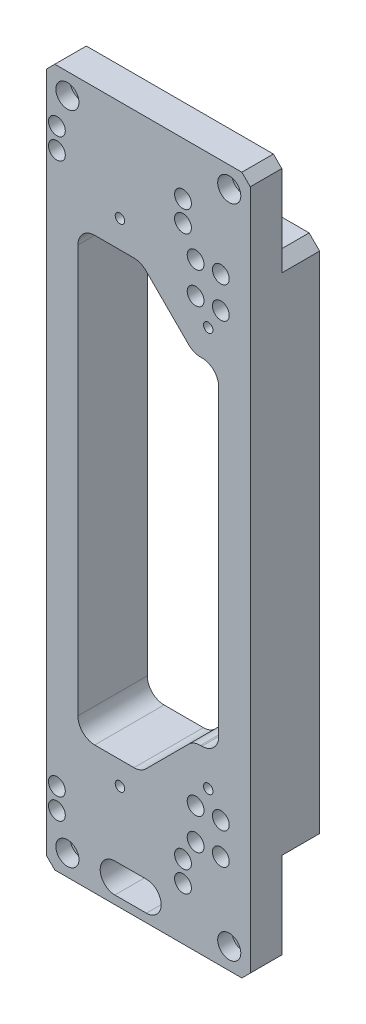
SolidWorks part; units mm, degrees
material "6061 Alloy"
ref_plane "Front Plane" through (0, 0, 0) normal (0, 0, 1) x (1, 0, 0)
ref_plane "Top Plane" through (0, 0, 0) normal (0, 1, 0) x (1, 0, 0)
ref_plane "Right Plane" through (0, 0, 0) normal (1, 0, 0) x (0, 0, -1)
sketch "Sketch1" plane through (0, 0, 0) normal (0, 0, 1) x (1, 0, 0)
  line L1 (48.5, -146) -> (-48.5, -146)
  line L2 (48.5, -146) -> (48.5, 146)
  line L3 (48.5, 146) -> (-48.5, 146)
  line L4 (-48.5, -146) -> (-48.5, 146)
  line L5 (48.5, -146) -> (-48.5, 146) construction
  line L6 (48.5, 146) -> (-48.5, -146) construction
  point P0 (0, 0)
  dimension "D1" = 292
  dimension "D3" = 97
extrude "Boss-Extrude1" add sketch "Sketch1" along normal blind 18 contours L4 L3 L2 L1
sketch "Sketch2" plane through (0, 0, 0) normal (0, 0, -1) x (-1, 0, 0)
  line L0 (-48.5, -146) -> (-48.5, 146) construction
  line L1 (-48.5, -146) -> (-21.5, -146)
  line L2 (-48.5, -146) -> (-48.5, -126)
  line L3 (-48.5, -126) -> (-21.5, -126)
  line L4 (-21.5, -146) -> (-21.5, -126)
  line L5 (-48.5, -146) -> (48.5, -146) construction
  line L6 (55, 0) -> (-55, 0) construction
  line L7 (-48.5, 124) -> (-21.5, 124)
  line L8 (-21.5, 146) -> (-21.5, 124)
  line L9 (-48.5, 146) -> (-21.5, 146)
  line L10 (-48.5, 146) -> (-48.5, 124)
  dimension "D1" = 20
  dimension "D2" = 27
  dimension "D3" = 22
extrude "Cut-Extrude1" cut sketch "Sketch2" against normal through all
sketch "Sketch3" plane through (0, 0, 18) normal (0, 0, 1) x (1, 0, 0)
  line L0 (-48.5, -146) -> (-48.5, 146) construction
  line L1 (48.5, -166) -> (-48.5, -166)
  line L2 (48.5, -166) -> (48.5, 166)
  line L3 (48.5, 166) -> (-48.5, 166)
  line L4 (-48.5, -166) -> (-48.5, 166)
  line L5 (48.5, -166) -> (-48.5, 166) construction
  line L6 (48.5, 166) -> (-48.5, -166) construction
  line L9 (21.5, 146) -> (-48.5, 146) construction
  point P0 (0, 0)
  dimension "D1" = 20
extrude "Boss-Extrude2" add sketch "Sketch3" along normal blind 15
chamfer "Chamfer1" distance 5 angle 45 6 edges at (21.5, -146, 9) (48.5, -126, 9) (21.5, 146, 9) (48.5, 124, 9) (-48.5, 146, 9) (-48.5, -146, 9)
fillet "Fillet1" radius 5 2 edges at (21.5, 124, 9) (21.5, -126, 9)
sketch "Sketch4" plane through (0, 0, 18) normal (0, 0, -1) x (-1, 0, 0)
  line L0 (0.9, -155) -> (15.9, -155) construction
  line L1 (0.9, -148) -> (15.9, -148)
  line L2 (0.9, -162) -> (15.9, -162)
  arc A0 (0.9, -148) -> (0.9, -162) centre (0.9, -155) ccw
  arc A1 (15.9, -162) -> (15.9, -148) centre (15.9, -155) ccw
  point P2 (8.4, -155)
  dimension "D2" = 7
  dimension "D1" = 15
  dimension "D3" = 155
  dimension "D4" = 8.4
extrude "Cut-Extrude2" cut sketch "Sketch4" against normal through all contours A1 L1 A0 L2
hole_wizard "CBORE for M4 Hexagon socket head cap screws1" positions "Sketch5" profile "Sketch6" counterbore size "M4" standard "GB" end condition through all
sketch "Sketch5" plane through (0, 0, 33) normal (0, 0, 1) x (1, 0, 0)
  line L0 (18.15, 0) -> (-18.15, 0) construction
  line L1 (-48.5, -1) -> (48.5, -1) construction
  line L2 (-48.5, 166) -> (-48.5, -166) construction
  line L3 (48.5, -166) -> (48.5, 166) construction
  point P0 (-43.5, -141)
  point P2 (-43.5, -131)
  point P4 (16.5, -131)
  point P6 (16.5, -141)
  point P11 (16.5, 141)
  point P12 (16.5, 131)
  point P13 (-43.5, 131)
  point P14 (-43.5, 141)
  point P24 (22.5, -121)
  point P26 (34.5, -121)
  point P28 (22.5, -106)
  point P30 (34.5, -106)
  point P49 (34.5, 104)
  point P50 (22.5, 104)
  point P51 (34.5, 119)
  point P52 (22.5, 119)
  dimension "D1" = 10
  dimension "D2" = 60
  dimension "D3" = 131
  dimension "D4" = 43.5
  dimension "D5" = 6
  dimension "D6" = 10
  dimension "D7" = 12
  dimension "D8" = 15
  dimension "D9" = 1
sketch "Sketch6" plane through (-43.5, -141, 33) normal (1, 0, 0) x (0, -1, 0)
  line L0 (0, 0) -> (0, 33)
  line L1 (0, 33) -> (2.25, 33)
  line L3 (2.25, 33) -> (2.25, 8)
  line L4 (2.25, 8) -> (4, 8)
  line L5 (4, 8) -> (4, 0)
  line L7 (4, 0) -> (0, 0)
  line L11 (0, -6.35) -> (0, 107.95) construction
  dimension "Thru Hole Dia." = 4.5
  dimension "Thru Hole Depth" = 33
  dimension "C'Bore Dia." = 8
  dimension "C'Bore Depth" = 8
hole_wizard "M4 Clearance Hole1" positions "Sketch7" profile "Sketch9" hole size "M4" standard "GB" end condition through all
sketch "Sketch7" plane through (0, 0, 33) normal (0, 0, 1) x (1, 0, 0)
  point P0 (28.5, -96)
  point P2 (-13.5, -116)
  point P4 (28.5, 94)
  point P6 (-13.5, 118)
  dimension "D1" = 94
  dimension "D2" = 96
  dimension "D3" = 116
  dimension "D4" = 118
  dimension "D5" = 13.5
  dimension "D6" = 28.5
sketch "Sketch9" plane through (28.5, -96, 33) normal (1, 0, 0) x (0, -1, 0)
  line L0 (0, 0) -> (0, 33)
  line L1 (0, 33) -> (2.25, 33)
  line L2 (2.25, 33) -> (2.25, 0)
  line L5 (2.25, 0) -> (0, 0)
  line L11 (0, -6.35) -> (0, 107.95) construction
  dimension "Thru Hole Dia." = 4.5
  dimension "Thru Hole Depth" = 33
hole_wizard "CBORE for M6 Slotted cheese head screws2" positions "Sketch10" profile "Sketch11" counterbore size "M6" standard "GB" end condition through all
sketch "Sketch10" plane through (0, 0, 33) normal (0, 0, 1) x (1, 0, 0)
  line L0 (18.15, 0) -> (-18.15, 0) construction
  line L1 (0, -18.15) -> (0, 18.15) construction
  line L2 (-48.5, 166) -> (-48.5, -166) construction
  line L4 (48.5, 166) -> (-48.5, 166) construction
  point P0 (-38.5, 156)
  point P8 (-38.5, -156)
  point P11 (38.5, -156)
  point P12 (38.5, 156)
  dimension "D1" = 10
  dimension "D2" = 10
sketch "Sketch11" plane through (-38.5, 156, 33) normal (1, 0, 0) x (0, -1, 0)
  line L0 (0, 0) -> (0, 33)
  line L1 (0, 33) -> (3.3, 33)
  line L3 (3.3, 33) -> (3.3, 6.8)
  line L4 (3.3, 6.8) -> (5.5, 6.8)
  line L5 (5.5, 6.8) -> (5.5, 0)
  line L7 (5.5, 0) -> (0, 0)
  line L11 (0, -6.35) -> (0, 107.95) construction
  dimension "Thru Hole Dia." = 6.6
  dimension "Thru Hole Depth" = 33
  dimension "C'Bore Dia." = 11
  dimension "C'Bore Depth" = 6.8
chamfer "Chamfer2" distance 4 angle 45 4 edges at (48.5, -166, 25.5) (-48.5, -166, 25.5) (48.5, 166, 25.5) (-48.5, 166, 25.5)
sketch "Sketch12" plane through (0, 0, 33) normal (0, 0, 1) x (1, 0, 0)
  line L0 (-33.5, -105) -> (-33.5, 105)
  line L1 (-33.5, 105) -> (-3.5, 105)
  line L2 (-3.5, 105) -> (21.5, 80)
  line L3 (21.5, 80) -> (33.5, 80)
  line L4 (33.5, 80) -> (33.5, -80)
  line L5 (18.15, 0) -> (-18.15, 0) construction
  line L6 (21.5, -80) -> (33.5, -80)
  line L7 (-3.5, -105) -> (21.5, -80)
  line L8 (-33.5, -105) -> (-3.5, -105)
  line L9 (-48.5, 162) -> (-48.5, -162) construction
  line L10 (48.5, -162) -> (48.5, 162) construction
  point P9 (33.5, 0)
  point P12 (-33.5, 0)
  dimension "D1" = 210
  dimension "D2" = 15
  dimension "D3" = 15
  dimension "D4" = 160
  dimension "D5" = 135
  dimension "D6" = 30
extrude "Cut-Extrude3" cut sketch "Sketch12" against normal through all
fillet "Fillet4" radius 8 8 edges at (21.5, 80, 16.5) (33.5, 80, 16.5) (33.5, -80, 16.5) (21.5, -80, 16.5) (-3.5, -105, 16.5) (-33.5, -105, 16.5) (-3.5, 105, 16.5) (-33.5, 105, 16.5)
sketch "Sketch13" plane through (0, 0, 0) normal (0, 0, -1) x (-1, 0, 0)
  line L0 (48.5, -141) -> (48.5, 141) construction
  line L1 (42.5, 87.5) -> (48.5, 87.5)
  line L2 (42.5, 87.5) -> (42.5, -87.5)
  line L3 (42.5, -87.5) -> (48.5, -87.5)
  line L4 (48.5, 87.5) -> (48.5, -87.5)
  line L5 (42.5, 87.5) -> (48.5, -87.5) construction
  line L6 (42.5, -87.5) -> (48.5, 87.5) construction
  point P0 (45.5, 0)
  dimension "D1" = 175
  dimension "D2" = 6
extrude "Cut-Extrude4" cut sketch "Sketch13" against normal blind 15
fillet "Fillet5" radius 3 2 edges at (-42.5, -87.5, 7.5) (-42.5, 87.5, 7.5)
